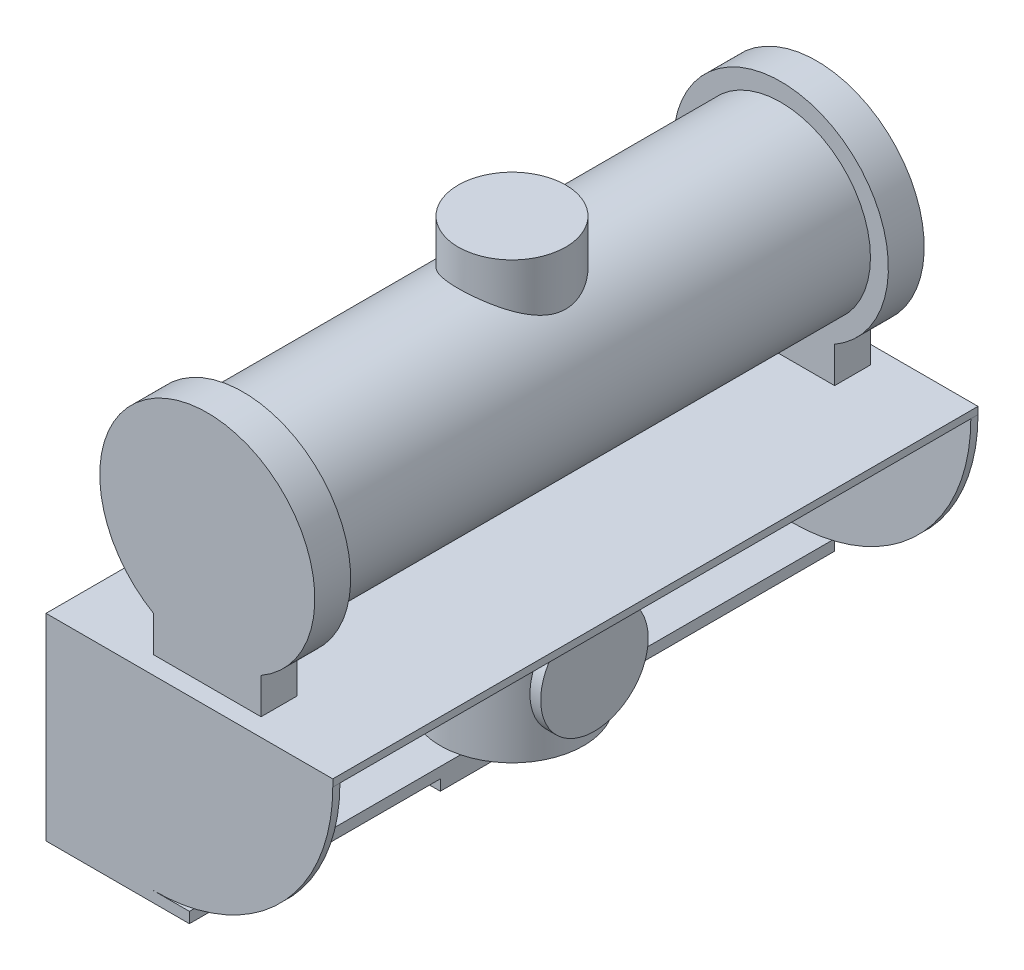
SolidWorks part; units mm, degrees
ref_plane "Front Plane" through (0, 0, 0) normal (0, 0, 1) x (1, 0, 0)
ref_plane "Top Plane" through (0, 0, 0) normal (0, 1, 0) x (1, 0, 0)
ref_plane "Right Plane" through (0, 0, 0) normal (1, 0, 0) x (0, 0, -1)
sketch "Sketch1" plane through (0, 0, 0) normal (0, 0, 1) x (1, 0, 0)
  circle A0 centre (0, 0) radius 25
  dimension "D1" = 50
extrude "Boss-Extrude1" add sketch "Sketch1" along normal blind 150
sketch "Sketch2" plane through (0, 0, 150) normal (0, 0, 1) x (1, 0, 0)
  circle A0 centre (0, 0) radius 30
  dimension "D1" = 60
extrude "Boss-Extrude2" add sketch "Sketch2" along normal blind 10
sketch "Sketch3" plane through (0, 0, 0) normal (0, 0, -1) x (-1, 0, 0)
  circle A0 centre (0, 0) radius 30
  dimension "D1" = 60
extrude "Boss-Extrude3" add sketch "Sketch3" along normal blind 10
ref_plane "Plane1" through (0, 25, 0) normal (0, 1, 0) x (1, 0, 0)
sketch "Sketch4" plane through (0, 25, 0) normal (0, 1, 0) x (1, 0, 0)
  circle A0 centre (0, -75) radius 15
  dimension "D1" = 30
  dimension "D2" = 75
extrude "Boss-Extrude4" add sketch "Sketch4" along normal mid plane 20
ref_plane "Plane2" through (0, 0, 160) normal (0, 0, -1) x (-1, 0, 0)
sketch "Sketch5" plane through (0, 0, 160) normal (0, 0, 1) x (1, 0, 0)
  line L0 (-15, -25.9808) -> (-15, -35.9808)
  line L1 (-15, -35.9808) -> (15, -35.9808)
  line L4 (15, -35.9808) -> (15, -25.9808)
  line L5 (15, -25.9808) -> (-15, -25.9808)
  circle A0 centre (0, 0) radius 30 construction
  dimension "D1" = 30
  dimension "D2" = 15
  dimension "D3" = 10
extrude "Boss-Extrude5" add sketch "Sketch5" against normal blind 10
ref_plane "Plane3" through (0, 0, 75) normal (0, 0, 1) x (1, 0, 0)
mirror "Mirror1" about plane through (0, 0, 75) normal (0, 0, 1) of "Boss-Extrude5"
sketch "Sketch6" plane through (0, -35.9808, 0) normal (0, -1, 0) x (-1, 0, 0)
  line L0 (15, -160) -> (-15, -160) construction
  line L1 (40, -165) -> (-40, -165)
  line L2 (40, -165) -> (40, 15)
  line L3 (40, 15) -> (-40, 15)
  line L4 (-40, -165) -> (-40, 15)
  line L6 (-25, 0) -> (-25, -150) construction
  dimension "D1" = 80
  dimension "D2" = 180
  dimension "D3" = 5
  dimension "D4" = 15
extrude "Boss-Extrude6" add sketch "Sketch6" along normal blind 2
sketch "Sketch7" plane through (0, -37.9808, 0) normal (0, -1, 0) x (-1, 0, 0)
  line L0 (-40, -165) -> (40, -165)
  line L1 (40, -165) -> (40, -163)
  line L2 (40, -165) -> (40, 15) construction
  line L3 (40, -163) -> (-40, -163)
  line L4 (-40, 15) -> (-40, -165) construction
  line L5 (-40, -163) -> (-40, -165)
  line L6 (40, -163) -> (38, -163)
  line L7 (38, -163) -> (38, 15)
  line L8 (40, 15) -> (-40, 15) construction
  line L9 (38, 15) -> (40, 15)
  line L10 (40, 15) -> (40, -163)
  line L11 (38, 15) -> (-40, 15)
  line L12 (-40, 15) -> (-40, 13)
  line L13 (-40, 13) -> (38, 13)
  line M4 (40, -165) -> (40, 15)
  line M5 (40, 15) -> (-40, 15)
  line M6 (-40, 15) -> (-40, -165)
  line M7 (-40, -165) -> (40, -165)
  dimension "D1" = 2
  dimension "D2" = 2
  dimension "D3" = 2
extrude "Boss-Extrude7" add sketch "Sketch7" along normal blind 50 contours L3 M4 M6 M7 | L7 L3 M4 M5 | L13 L7 M6 M5
fillet "Fillet1" radius 50 2 edges at (40, -87.9808, -14) (40, -87.9808, 164)
sketch "Sketch8" plane through (0, -37.9808, 0) normal (0, -1, 0) x (-1, 0, 0)
  circle A1 centre (0, -75) radius 20
  dimension "D2" = 40
extrude "Boss-Extrude8" add sketch "Sketch8" along normal blind 45
ref_plane "Plane4" through (20, 0, 0) normal (1, 0, 0) x (0, 0, -1)
sketch "Sketch10" plane through (20, 0, 0) normal (1, 0, 0) x (0, 0, -1)
  line L1 (-95, -37.9808) -> (-55, -37.9808) construction
  line L4 (-95, -37.9808) -> (-95, -82.9808) construction
  circle A1 centre (-75, -62.9808) radius 15
  dimension "D3" = 30
  dimension "D5" = 25
  dimension "D8" = 20
extrude "Boss-Extrude9" add sketch "Sketch10" along normal blind 3 separate body contours A1
sketch "Sketch11" plane through (-40, 0, 0) normal (-1, 0, 0) x (0, 0, 1)
  line L0 (-15, -87.9808) -> (165, -87.9808)
  line L1 (165, -87.9808) -> (165, -90.9808)
  line L2 (165, -90.9808) -> (-15, -90.9808)
  line L3 (-15, -90.9808) -> (-15, -87.9808)
  dimension "D1" = 3
extrude "Boss-Extrude10" add sketch "Sketch11" against normal blind 40
sketch "Sketch12" plane through (0, -90.9808, 0) normal (0, -1, 0) x (-1, 0, 0)
  line L0 (0, 15) -> (0, -165) construction
  line L1 (0, -55) -> (40, -55)
  line L2 (0, -55) -> (0, -95)
  line L3 (0, -95) -> (40, -95)
  line L4 (40, -55) -> (40, -95)
  line L5 (40, 15) -> (40, -165) construction
  circle A0 centre (0, -75) radius 20 construction
  dimension "D4" = 20
  dimension "D1" = 0
  dimension "D2" = 0
  dimension "D3" = 40
extrude "Boss-Extrude11" add sketch "Sketch12" along normal blind 3
